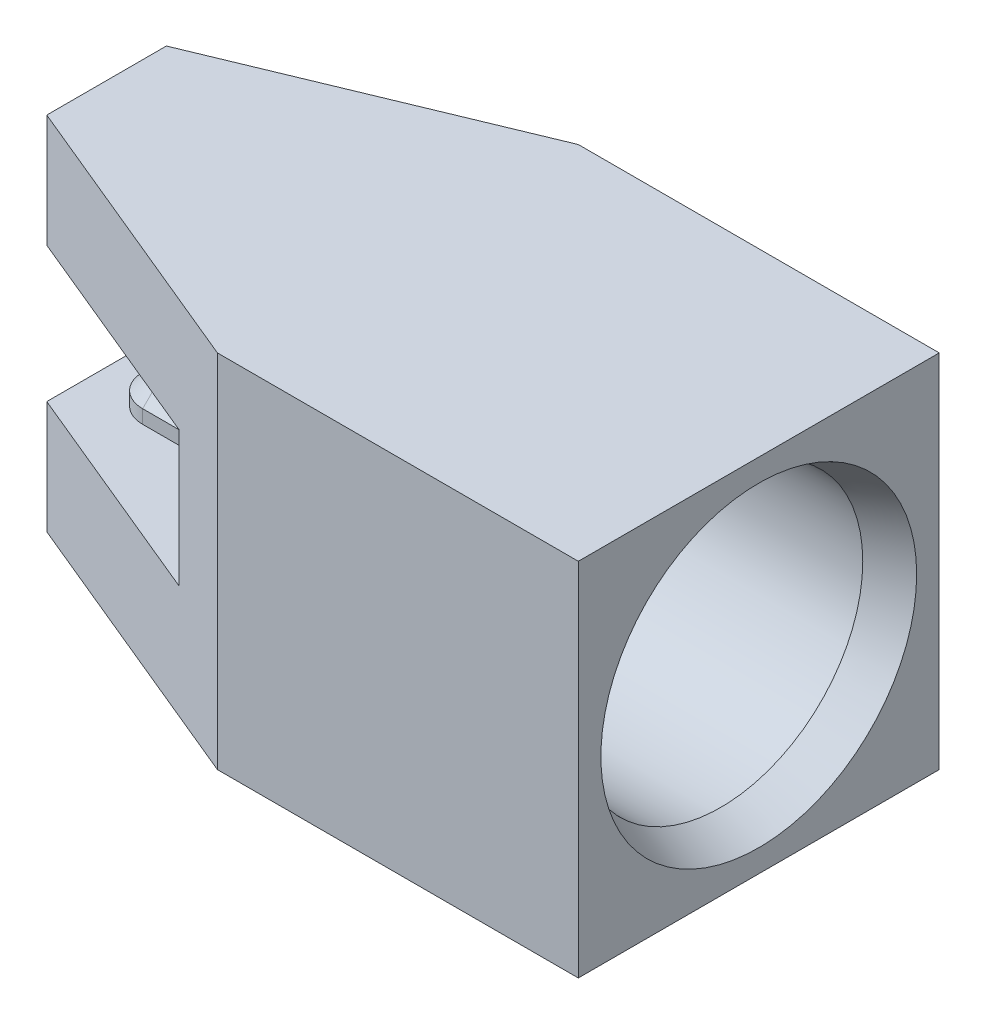
SolidWorks part; units mm, degrees
ref_plane "Ebene vorne" through (0, 0, 0) normal (0, 0, 1) x (1, 0, 0)
ref_plane "Ebene oben" through (0, 0, 0) normal (0, 1, 0) x (1, 0, 0)
ref_plane "Ebene rechts" through (0, 0, 0) normal (1, 0, 0) x (0, 0, -1)
sketch "Skizze1" plane through (0, 0, 0) normal (0, 1, 0) x (1, 0, 0)
  line L0 (2.9564, 1.2246) -> (9.6569, 4)
  line L2 (9.6569, -4) -> (2.9564, -1.2246)
  line L3 (9.6569, 4) -> (17.6569, 4)
  line L4 (17.6569, 4) -> (17.6569, -4)
  line L5 (17.6569, -4) -> (9.6569, -4)
  arc A0 (2.9564, -1.2246) -> (2.9564, 1.2246) centre (0, 0) ccw
  point P9 (17.6569, 0)
  dimension "D1" = 6.4
  dimension "D2" = 45
  dimension "D3" = 8
  dimension "D4" = 8
extrude "Aufsatz-Linear austragen1" add sketch "Skizze1" along normal mid plane 8
sketch "Skizze2" plane through (0, 0, 0) normal (0, 0, 1) x (1, 0, 0)
  line L5 (0, 1.5) -> (8.2, 1.5)
  line L6 (0, 1.5) -> (0, -1.5)
  line L7 (0, -1.5) -> (8.2, -1.5)
  line L8 (8.2, 1.5) -> (8.2, -1.5)
  point P4 (0, 0)
  dimension "D1" = 1.5
  dimension "D2" = 8.2
extrude "Schnitt-Linear austragen1" cut sketch "Skizze2" against normal through all both and the other way through all
sketch "Skizze7" plane through (0, 1.5, 0) normal (0, -1, 0) x (1, 0, 0)
  line L0 (4.7, 0) -> (5.5, 0) construction
  line L1 (4.7, 0.7) -> (5.5, 0.7)
  line L2 (4.7, -0.7) -> (5.5, -0.7)
  arc A0 (4.7, 0.7) -> (4.7, -0.7) centre (4.7, 0) ccw
  arc A1 (5.5, -0.7) -> (5.5, 0.7) centre (5.5, 0) ccw
  point P3 (5.1, 0)
  dimension "D1" = 4
  dimension "D2" = 6.2
  dimension "D3" = 1.4
extrude "Aufsatz-Linear austragen2" add sketch "Skizze7" along normal blind 0.6
chamfer "Fase1" distance 0.3 angle 45 4 edges at (5.1, 0.9, -0.7) (6.2, 0.9, 0) (4, 0.9, 0) (5.1, 0.9, 0.7)
mirror "Spiegeln1" about plane through (0, 0, 0) normal (0, 1, 0) of "Aufsatz-Linear austragen2", "Fase1"
sketch "Skizze10" plane through (0, 0, 0) normal (0, 1, 0) x (1, 0, 0)
  line L0 (17.6569, 4) -> (9.6569, 4) construction
  line L1 (0, 4) -> (3.2, 4)
  line L2 (0, 4) -> (0, -4)
  line L3 (0, -4) -> (3.2, -4)
  line L4 (3.2, 4) -> (3.2, -4)
  line L5 (9.6569, -4) -> (17.6569, -4) construction
  arc A0 (2.9564, -1.2246) -> (2.9564, 1.2246) centre (0, 0) ccw construction
extrude "Schnitt-Linear austragen2" cut sketch "Skizze10" against normal through all both and the other way through all
hole_wizard "Ø6.3 (6.3) Durchmesser Bohrung1" positions "Skizze11" profile "Skizze13" hole size "Ø6.3" standard "ISO"
sketch "Skizze11" plane through (17.6569, 0, 0) normal (1, 0, 0) x (0, 0, -1)
  point P0 (0, 0)
sketch "Skizze13" plane through (17.6569, 0, 0) normal (0, 1, 0) x (0, 0, -1)
  line L0 (0, 0) -> (0, 9.3927)
  line L1 (0, 9.3927) -> (3.15, 7.5)
  line L2 (3.15, 7.5) -> (3.15, 0.845)
  line L3 (3.15, 0.845) -> (3.5, 0)
  line L5 (3.5, 0) -> (0, 0)
  line L6 (-3.15, 0.845) -> (-3.5, 0) construction
  line L10 (0, 9.3927) -> (-3.15, 7.5) construction
  line L11 (0, -6.35) -> (0, 107.95) construction
  dimension "Bohrerdurchmesser" = 6.3
  dimension "Bohrungstiefe" = 7.5
  dimension "Senkdurchmesser2 (Oben)" = 7
  dimension "Senkwinkel2 (Oben)" = 45
  dimension "Spitzenwinkel" = 118
